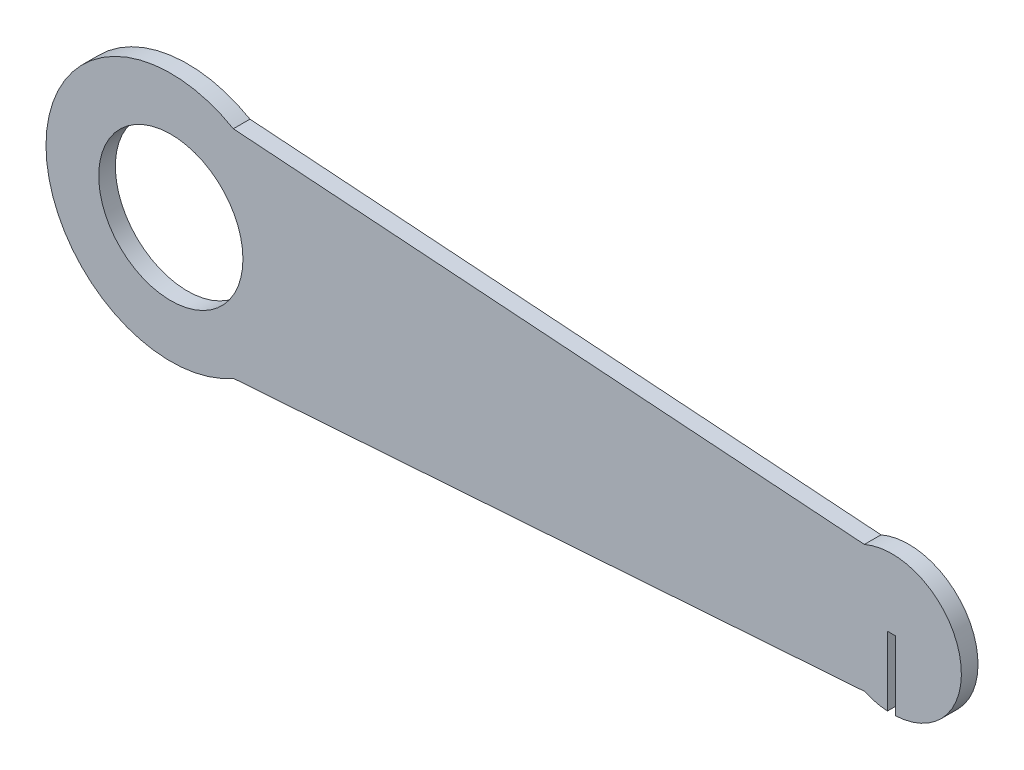
SolidWorks part; units mm, degrees
ref_plane "Front Plane" through (0, 0, 0) normal (0, 0, 1) x (1, 0, 0)
ref_plane "Top Plane" through (0, 0, 0) normal (0, 1, 0) x (1, 0, 0)
ref_plane "Right Plane" through (0, 0, 0) normal (1, 0, 0) x (0, 0, -1)
sketch "Sketch1" plane through (0, 0, 0) normal (0, 0, 1) x (1, 0, 0)
  line L0 (0, 0) -> (130, 0) construction
  line L1 (125.0123, 11.4618) -> (11.2644, 19.4772)
  line L2 (129.1697, 0) -> (130.6697, 0)
  line L3 (129.1697, 0) -> (129.1697, -12.4724)
  line L4 (125.0123, -11.4618) -> (11.2644, -19.4772)
  line L5 (130.6697, 0) -> (130.6697, -12.482)
  circle A0 centre (0, 0) radius 13
  arc A1 (11.2644, 19.4772) -> (11.2644, -19.4772) centre (0, 0) ccw
  arc A2 (130.6697, -12.482) -> (125.0123, 11.4618) centre (130, 0) ccw
  arc A3 (125.0123, -11.4618) -> (129.1697, -12.4724) centre (130, 0) ccw
  dimension "D1" = 26
  dimension "D2" = 45
  dimension "D4" = 25
  dimension "D3" = 130
  dimension "D6" = 1.5
  dimension "D7" = 11.2644
  dimension "D9" = 125.0123
  dimension "D10" = 129.1697
extrude "Boss-Extrude1" add sketch "Sketch1" along normal blind 3
